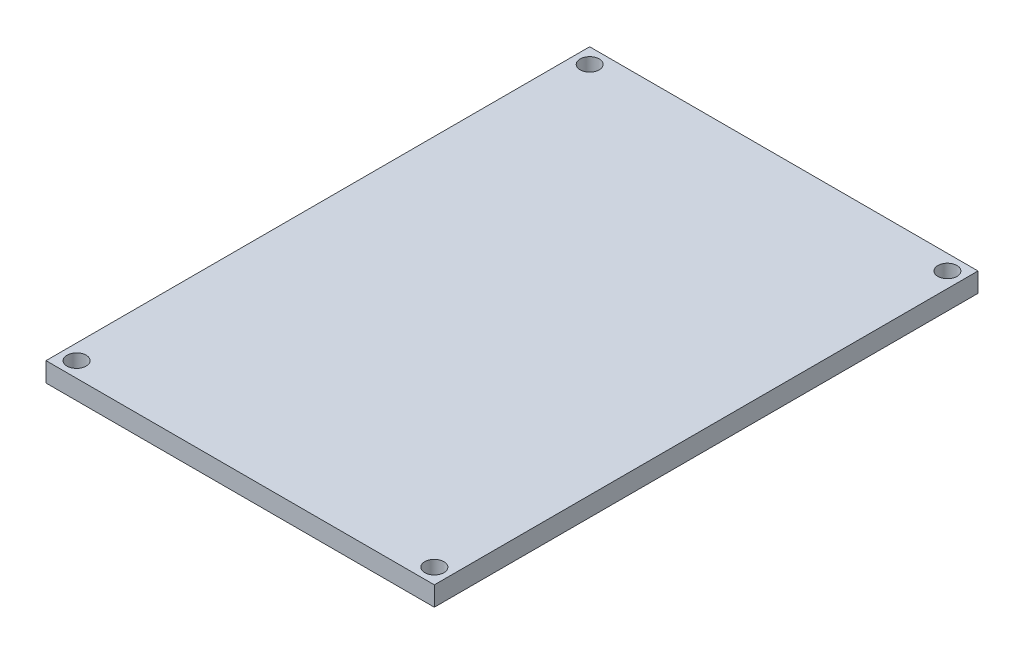
SolidWorks part; units mm, degrees
ref_plane "Front Plane" through (0, 0, 0) normal (0, 0, 1) x (1, 0, 0)
ref_plane "Top Plane" through (0, 0, 0) normal (0, 1, 0) x (1, 0, 0)
ref_plane "Right Plane" through (0, 0, 0) normal (1, 0, 0) x (0, 0, -1)
sketch "Sketch1" plane through (0, 0, 0) normal (0, 1, 0) x (1, 0, 0)
  line L1 (-43.7579, 27.0488) -> (7.0421, 27.0488)
  line L2 (-43.7579, 27.0488) -> (-43.7579, -44.0712)
  line L3 (-43.7579, -44.0712) -> (7.0421, -44.0712)
  line L4 (7.0421, 27.0488) -> (7.0421, -44.0712)
  dimension "D1" = 50.8
  dimension "D2" = 71.12
extrude "Boss-Extrude1" add sketch "Sketch1" along normal blind 2.54
sketch "Sketch2" plane through (0, 2.54, 0) normal (0, 1, 0) x (1, 0, 0)
  line L0 (-41.7579, 27.0488) -> (-43.7579, 27.0488)
  line L1 (7.0421, 27.0488) -> (-43.7579, 27.0488) construction
  line L2 (-43.7579, 27.0488) -> (-43.7579, 25.0488)
  line L3 (-43.7579, 27.0488) -> (-43.7579, -44.0712) construction
  line L4 (-43.7579, 25.0488) -> (7.0421, 25.0488) construction
  line L5 (7.0421, -44.0712) -> (7.0421, 27.0488) construction
  line L6 (-41.7579, 27.0488) -> (-41.7579, -44.0712) construction
  line L7 (-43.7579, -44.0712) -> (7.0421, -44.0712) construction
  line L8 (7.0421, 27.0488) -> (5.0421, 27.0488)
  line L9 (5.0421, 27.0488) -> (5.0421, -44.0712) construction
  line L10 (-43.7579, -44.0712) -> (-43.7579, -42.0712)
  line L11 (7.0421, -44.0712) -> (7.0421, -42.0712)
  line L12 (-43.7579, -42.0712) -> (7.0421, -42.0712) construction
  circle A0 centre (-41.7579, -42.0712) radius 1.2487
  circle A1 centre (5.0421, -42.0712) radius 1.2519
  circle A2 centre (5.0421, 25.0488) radius 1.2465
  circle A3 centre (-41.7579, 25.0488) radius 1.2456
  dimension "D1" = 2
  dimension "D2" = 2
  dimension "D3" = 2
  dimension "D4" = 2
extrude "Cut-Extrude1" cut sketch "Sketch2" against normal through all contours A3 | A2 | A0 | A1
